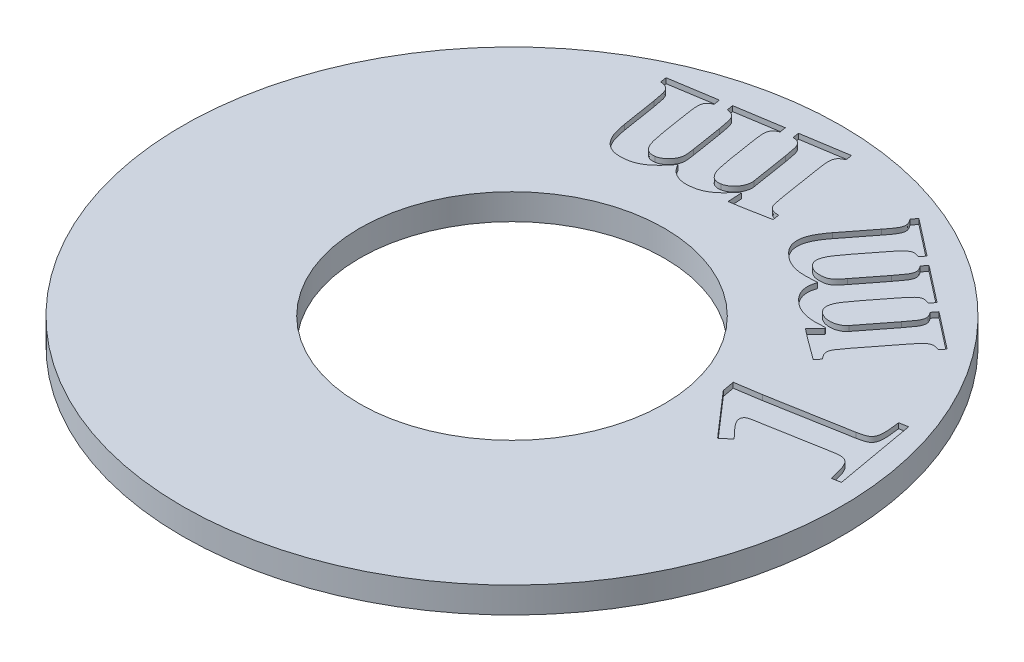
SolidWorks part; units mm, degrees
ref_plane "Front Plane" through (0, 0, 0) normal (0, 0, 1) x (1, 0, 0)
ref_plane "Top Plane" through (0, 0, 0) normal (0, 1, 0) x (1, 0, 0)
ref_plane "Right Plane" through (0, 0, 0) normal (1, 0, 0) x (0, 0, -1)
sketch "Sketch1" plane through (0, 0, 0) normal (0, 1, 0) x (1, 0, 0)
  circle A0 centre (0, 0) radius 12.7
  dimension "D1" = 25.4
extrude "Boss-Extrude1" add sketch "Sketch1" along normal blind 1
sketch "Sketch2" plane through (0, 0, 0) normal (0, -1, 0) x (-1, 0, 0)
  circle A0 centre (0, 0) radius 5.8674
  dimension "D1" = 11.7348
extrude "Cut-Extrude1" cut sketch "Sketch2" against normal through all
sketch "Sketch4" plane through (0, 1, 0) normal (0, 1, 0) x (1, 0, 0)
  circle A0 centre (0, 0) radius 12.0429 construction
  text T0 "<b>1mm</b>" font "Cambria" height 5.08
extrude "Cut-Extrude2" cut sketch "Sketch4" against normal blind 0.2
